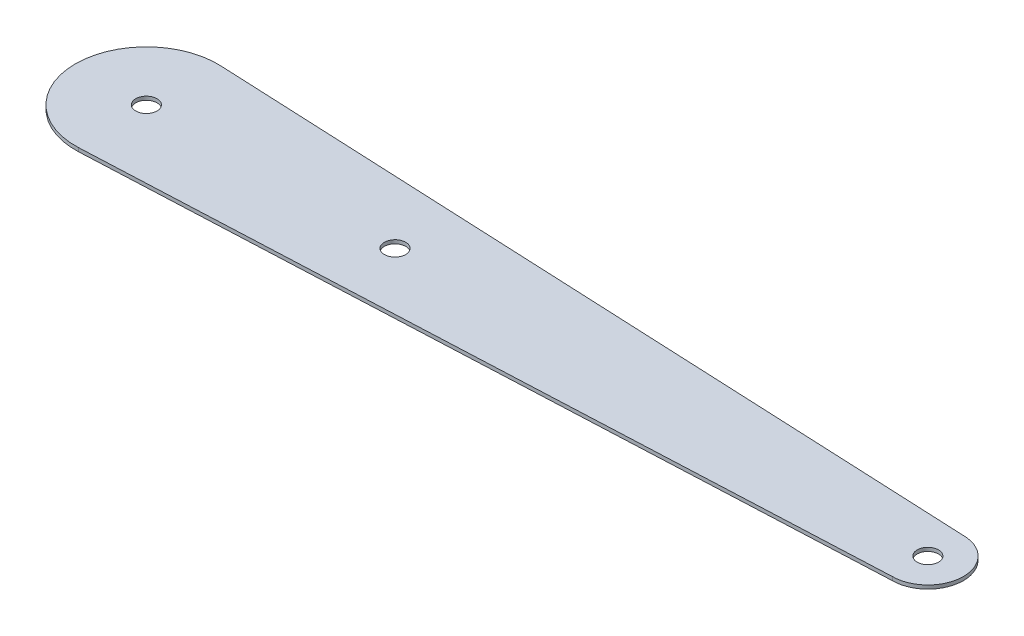
SolidWorks part; units mm, degrees
ref_plane "Front Plane" through (0, 0, 0) normal (0, 0, 1) x (1, 0, 0)
ref_plane "Top Plane" through (0, 0, 0) normal (0, 1, 0) x (1, 0, 0)
ref_plane "Right Plane" through (0, 0, 0) normal (1, 0, 0) x (0, 0, -1)
sketch "Sketch1" plane through (0, 0, 0) normal (0, 1, 0) x (1, 0, 0)
  line L0 (-247.7249, 49.9482) -> (300, 25)
  line L5 (300, -25) -> (-247.7249, -49.9482)
  line L6 (-250, 0) -> (300, 0) construction
  arc A0 (-247.7249, 49.9482) -> (-247.7249, -49.9482) centre (-250, 0) ccw
  arc A1 (300, -25) -> (300, 25) centre (300, 0) ccw
  point P0 (-265.3248, -55.4012)
  point P4 (147.05, 75.833)
  point P5 (212.9789, 25)
  point P11 (212.9789, -25)
  point P12 (-211.3153, -50)
  point P13 (-215.076, 50)
  dimension "D1" = 100
  dimension "D2" = 50
  dimension "D3" = 550
  dimension "D4" = 250
extrude "Boss-Extrude1" add sketch "Sketch1" along normal blind 2.54
sketch "Sketch2" plane through (0, 2.54, 0) normal (0, 1, 0) x (1, 0, 0)
  line L0 (-75, 0) -> (0, 0) construction
  circle A0 centre (-75, 0) radius 7.5
  circle A1 centre (300, 0) radius 7.5
  arc A2 (300, -25) -> (300, 25) centre (300, 0) ccw construction
  circle A3 centre (-250, 0) radius 7.5
  arc A4 (-247.7249, 49.9482) -> (-247.7249, -49.9482) centre (-250, 0) ccw construction
  dimension "D2" = 15
  dimension "D1" = 75
extrude "Cut-Extrude1" cut sketch "Sketch2" against normal blind 10
